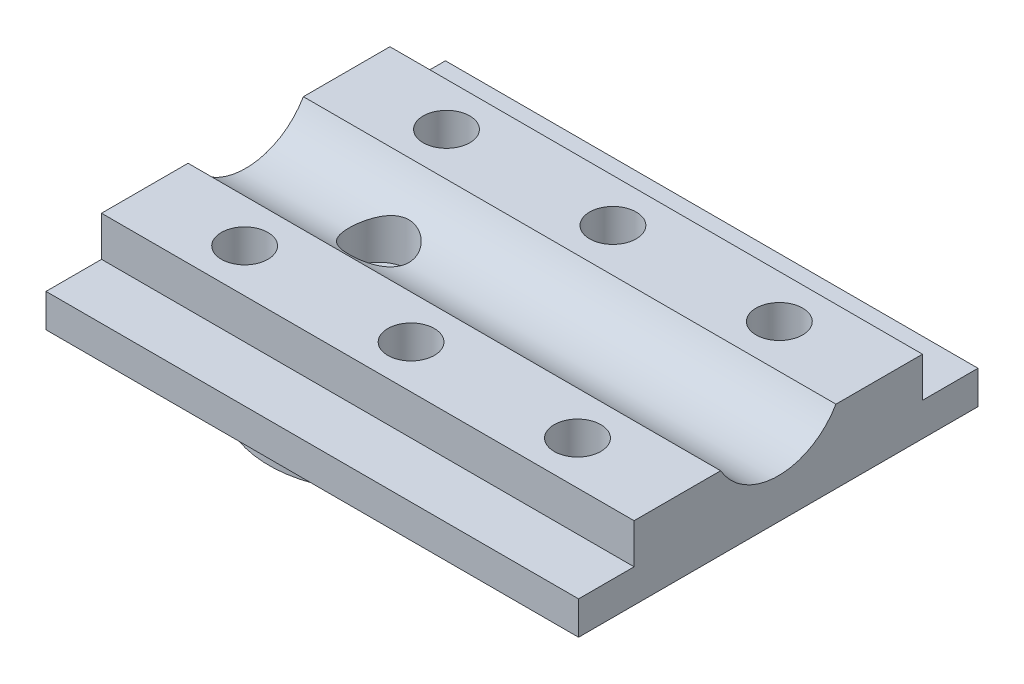
SolidWorks part; units mm, degrees
material "PETG"
ref_plane "Спереди" through (0, 0, 0) normal (0, 0, 1) x (1, 0, 0)
ref_plane "Сверху" through (0, 0, 0) normal (0, 1, 0) x (1, 0, 0)
ref_plane "Справа" through (0, 0, 0) normal (1, 0, 0) x (0, 0, -1)
sketch "Эскиз1" plane through (0, 0, 0) normal (0, 1, 0) x (1, 0, 0)
  line L1 (20, 15) -> (-20, 15)
  line L2 (20, 15) -> (20, -15)
  line L3 (20, -15) -> (-20, -15)
  line L4 (-20, 15) -> (-20, -15)
  line L5 (20, 15) -> (-20, -15) construction
  line L6 (20, -15) -> (-20, 15) construction
  point P0 (0, 0)
  dimension "D1" = 40
  dimension "D2" = 30
extrude "Бобышка-Вытянуть1" add sketch "Эскиз1" along normal blind 2.5
sketch "Эскиз2" plane through (0, 0, 0) normal (0, -1, 0) x (1, 0, 0)
  line L0 (-10, 0) -> (-10, -50000) construction
  line L1 (-13.1, 5.427) -> (-13.1, -5.427)
  line L2 (-6.9, 5.427) -> (-6.9, -5.427)
  line L3 (0, 0) -> (50000, 0) construction
  line L4 (-20, -15) -> (-20, 15) construction
  circle A0 centre (-10, 0) radius 8.25
  arc A1 (-13.1, -5.427) -> (-6.9, -5.427) centre (-10, 0) ccw
  arc A2 (-6.9, 5.427) -> (-13.1, 5.427) centre (-10, 0) ccw
  dimension "D1" = 12.5
  dimension "D2" = 2
  dimension "D3" = 6.2
  dimension "D4" = 10
extrude "Бобышка-Вытянуть2" add sketch "Эскиз2" along normal blind 7.2
sketch "Эскиз3" plane through (0, -7.2, 0) normal (0, -1, 0) x (1, 0, 0)
  circle A0 centre (-10, 0) radius 6.25
  arc A1 (-6.9, 5.427) -> (-13.1, 5.427) centre (-10, 0) ccw construction
extrude "Вырез-Вытянуть1" cut sketch "Эскиз3" against normal blind 2
sketch "Эскиз8" plane through (0, 0, 0) normal (0, -1, 0) x (1, 0, 0)
  line L2 (-13.1, 5.427) -> (-13.1, -5.427)
  line L3 (-6.9, -5.427) -> (-6.9, 5.427)
  line L4 (-13.1, 5.427) -> (-13.1, -5.427)
  line L5 (-6.9, -5.427) -> (-6.9, 5.427)
  arc A2 (-6.9, 5.427) -> (-13.1, 5.427) centre (-10, 0) ccw
  arc A3 (-13.1, -5.427) -> (-6.9, -5.427) centre (-10, 0) ccw
  arc A4 (-6.9, 5.427) -> (-13.1, 5.427) centre (-10, 0) ccw
  arc A5 (-13.1, -5.427) -> (-6.9, -5.427) centre (-10, 0) ccw
  dimension "D1" = 0
extrude "Бобышка-Вытянуть4" add sketch "Эскиз8" along normal blind 1.2
sketch "Эскиз4" plane through (0, 2.5, 0) normal (0, -1, 0) x (1, 0, 0)
  circle A0 centre (-10, 0) radius 1.15
  arc A1 (-13.1, -5.427) -> (-6.9, 5.427) centre (-10, 0) ccw construction
  dimension "D1" = 2.3
extrude "Вырез-Вытянуть2" cut sketch "Эскиз4" along normal up to surface (3.7 mm away) up to face at (-10, -1.2, 0)
sketch "Эскиз6" plane through (0, -5.2, 0) normal (0, -1, 0) x (1, 0, 0)
  line L0 (-25, 0) -> (-50025, 0) construction
  line L1 (-13.1, 5.427) -> (-13.1, -5.427) construction
  line L2 (-13.6, 1.25) -> (-13.1, 1.25) construction
  line L3 (-14.1, 0.75) -> (-14.1, -0.75) construction
  line L4 (-13.6, -1.25) -> (-13.1, -1.25) construction
  line L5 (-13.1, 1.25) -> (-13.1, -1.25)
  line L6 (-14.1, 1.25) -> (-13.1, -1.25) construction
  line L7 (-14.1, -1.25) -> (-13.1, 1.25) construction
  line L8 (-13.6, 1.25) -> (-14.1, 0.75) construction
  line L9 (-14.1, -0.75) -> (-13.6, -1.25) construction
  line L10 (-13.6828, -1.45) -> (-13.1, -1.45)
  line L11 (-14.3, -0.8328) -> (-13.6828, -1.45)
  line L12 (-14.3, 0.8328) -> (-14.3, -0.8328)
  line L13 (-13.6828, 1.45) -> (-14.3, 0.8328)
  line L14 (-13.6828, 1.45) -> (-13.1, 1.45)
  line L15 (-13.1, 1.45) -> (-13.1, 1.25)
  line L16 (-13.1, -1.45) -> (-13.1, -1.25)
  point P3 (-13.6, 0)
  dimension "D1" = 1
  dimension "D2" = 2.5
  dimension "D3" = 0.2
extrude "Вырез-Вытянуть4" cut sketch "Эскиз6" against normal up to surface (4 mm away) up to face at (-10, -1.2, -1.15)
chamfer "Фаска1" distance 0.2 angle 45 2 edges at (-13.1, -3.2, -1.45) (-13.1, -3.2, 1.45)
sketch "Эскиз10" plane through (-20, 0, 0) normal (-1, 0, 0) x (0, 0, 1)
  line L0 (0, 0) -> (0, 50000) construction
  line L1 (-5.8301, 5.5) -> (-5.8301, 2.5)
  line L2 (-15, 2.5) -> (15, 2.5) construction
  line L3 (-5.8301, 2.5) -> (5.8301, 2.5)
  line L4 (-5.8301, 5.5) -> (-4.3301, 5.5)
  line L5 (5.8301, 5.5) -> (5.8301, 2.5)
  line L6 (5.8301, 5.5) -> (4.3301, 5.5)
  arc A0 (-4.3301, 5.5) -> (4.3301, 5.5) centre (0, 8) ccw
  point P10 (3.7086, 5.5)
  point P11 (0, 10.6567)
  point P13 (0, 2.5)
  dimension "D1" = 5
  dimension "D3" = 0.5
  dimension "D2" = 3
  dimension "D4" = 1.5
extrude "Бобышка-Вытянуть5" add sketch "Эскиз10" against normal up to surface (40 mm away) up to face at (20, 1.25, 0)
sketch "Эскиз9" plane through (0, 2.5, 0) normal (0, 1, 0) x (1, 0, 0)
  circle A0 centre (-10, 0) radius 2.25
  dimension "D1" = 4.5
extrude "Вырез-Вытянуть5" cut sketch "Эскиз9" against normal blind 2.2 and the other way up to surface other way up to face at (0, 4.25, 0)
sketch "Эскиз13" plane through (0, 2.5, 0) normal (0, 1, 0) x (1, 0, 0)
  line L0 (0, 0) -> (-50000, 0) construction
  line L1 (20, 5.8301) -> (20, 15) construction
  line L2 (-20, 5.8301) -> (20, 5.8301)
  line L3 (-20, 5.8301) -> (-20, 10.8301)
  line L4 (-20, 10.8301) -> (20, 10.8301)
  line L5 (20, 5.8301) -> (20, 10.8301)
  line L6 (-20, -10.8301) -> (20, -10.8301)
  line L7 (20, -5.8301) -> (20, -10.8301)
  line L8 (-20, -5.8301) -> (20, -5.8301)
  line L9 (-20, -5.8301) -> (-20, -10.8301)
  line L10 (20, 4.3301) -> (-20, 4.3301) construction
  dimension "D1" = 6.5
extrude "Бобышка-Вытянуть6" add sketch "Эскиз13" along normal up to surface (3 mm away) up to face at (0, 5.5, 5.0801)
sketch "Эскиз14" plane through (0, 5.5, 0) normal (0, 1, 0) x (1, 0, 0)
  line L0 (0, 0) -> (-50000, 0) construction
  line L1 (-20, 7.5801) -> (20, 7.5801) construction
  line L2 (-20, 4.3301) -> (-20, 10.8301) construction
  line L3 (20, 10.8301) -> (20, 4.3301) construction
  line L4 (0, 0) -> (0, 50000) construction
  circle A0 centre (-12.5, 7.5801) radius 1.75
  circle A2 centre (12.5, 7.5801) radius 1.75
  circle A3 centre (0, 7.5801) radius 1.75
  circle A4 centre (12.5, -7.5801) radius 1.75
  circle A5 centre (0, -7.5801) radius 1.75
  circle A6 centre (-12.5, -7.5801) radius 1.75
  point P17 (0, 0)
  dimension "D1" = 3.5
  dimension "D2" = 25
extrude "Вырез-Вытянуть7" cut sketch "Эскиз14" against normal blind 4
